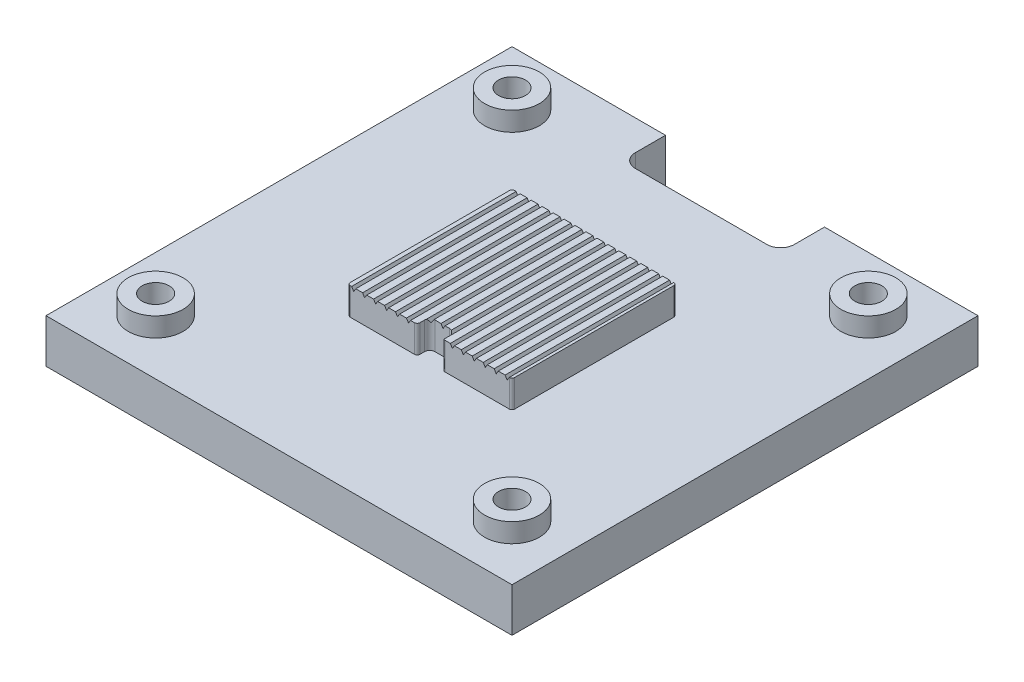
SolidWorks part; units mm, degrees
ref_plane "Front Plane" through (0, 0, 0) normal (0, 0, 1) x (1, 0, 0)
ref_plane "Top Plane" through (0, 0, 0) normal (0, 1, 0) x (1, 0, 0)
ref_plane "Right Plane" through (0, 0, 0) normal (1, 0, 0) x (0, 0, -1)
sketch "Sketch1" plane through (0, 0, 0) normal (0, 1, 0) x (1, 0, 0)
  line L0 (-7.15, 0) -> (7.15, 0) construction
  line L1 (-42.5, 42.5) -> (42.5, 42.5)
  line L2 (-42.5, 42.5) -> (-42.5, -42.5)
  line L3 (-42.5, -42.5) -> (42.5, -42.5)
  line L4 (42.5, 42.5) -> (42.5, -42.5)
  line L5 (-42.5, 42.5) -> (42.5, -42.5) construction
  line L6 (-42.5, -42.5) -> (42.5, 42.5) construction
  line L7 (0, -7.15) -> (0, 7.15) construction
  circle A0 centre (-32.5, 32.5) radius 2.4575
  circle A1 centre (-32.5, -32.5) radius 2.4575
  circle A2 centre (32.5, -32.5) radius 2.4575
  circle A3 centre (32.5, 32.5) radius 2.4575
  point P0 (0, 0)
  dimension "D3" = 4.915
  dimension "D1" = 85
  dimension "D2" = 85
  dimension "D4" = 10
  dimension "D5" = 10
extrude "Boss-Extrude1" add sketch "Sketch1" along normal blind 8
sketch "Sketch2" plane through (0, 0, 0) normal (0, -1, 0) x (1, 0, 0)
  line L0 (0, -7.15) -> (0, 7.15) construction
  line L1 (7.15, 0) -> (-7.15, 0) construction
  circle A0 centre (-32.5, 32.5) radius 3.969
  circle A1 centre (32.5, 32.5) radius 3.969
  circle A2 centre (32.5, -32.5) radius 3.969
  circle A3 centre (-32.5, -32.5) radius 3.969
  dimension "D1" = 7.938
extrude "Cut-Extrude1" cut sketch "Sketch2" against normal blind 4.166
sketch "Sketch3" plane through (0, 8, 0) normal (0, 1, 0) x (1, 0, 0)
  line L0 (0, -7.15) -> (0, 7.15) construction
  line L1 (-7.15, 0) -> (7.15, 0) construction
  circle A0 centre (32.5, -32.5) radius 5
  circle A1 centre (32.5, -32.5) radius 2.4575
  circle A2 centre (32.5, -32.5) radius 2.4575 construction
  circle A3 centre (-32.5, -32.5) radius 2.4575
  circle A4 centre (-32.5, -32.5) radius 5
  circle A5 centre (-32.5, 32.5) radius 5
  circle A6 centre (-32.5, 32.5) radius 2.4575
  circle A7 centre (32.5, 32.5) radius 2.4575
  circle A8 centre (32.5, 32.5) radius 5
  dimension "D1" = 10
extrude "Boss-Extrude2" add sketch "Sketch3" along normal blind 3.5
sketch "Sketch4" plane through (0, 8, 0) normal (0, 1, 0) x (1, 0, 0)
  line L0 (2.2929, -14.5) -> (2.2929, -13.7071)
  line L1 (14.5, -15) -> (2.7929, -15)
  line L2 (15, -14.5) -> (15, 14.5)
  line L3 (14.5, 15) -> (-14.5, 15)
  line L4 (-15, -14.5) -> (-15, 14.5)
  line L5 (15, -15) -> (-15, 15) construction
  line L6 (15, 15) -> (-15, -15) construction
  line L7 (1.2929, -12.7071) -> (-1.2929, -12.7071)
  line L8 (-2.2929, -13.7071) -> (-2.2929, -14.5)
  line L9 (-2.7929, -15) -> (-14.5, -15)
  arc A0 (-14.5, 15) -> (-15, 14.5) centre (-14.5, 14.5) ccw
  arc A1 (15, 14.5) -> (14.5, 15) centre (14.5, 14.5) ccw
  arc A2 (-14.5, -15) -> (-15, -14.5) centre (-14.5, -14.5) cw
  arc A3 (14.5, -15) -> (15, -14.5) centre (14.5, -14.5) ccw
  arc A4 (-2.2929, -14.5) -> (-2.7929, -15) centre (-2.7929, -14.5) cw
  arc A5 (2.2929, -14.5) -> (2.7929, -15) centre (2.7929, -14.5) ccw
  arc A6 (-1.2929, -12.7071) -> (-2.2929, -13.7071) centre (-1.2929, -13.7071) ccw
  arc A7 (2.2929, -13.7071) -> (1.2929, -12.7071) centre (1.2929, -13.7071) ccw
  point P0 (0, 0)
  point P10 (0, -12.7071)
  point P25 (-2.2929, -15)
  point P30 (-2.2929, -12.7071)
  point P33 (2.2929, -12.7071)
  dimension "D4" = 0.5
  dimension "D6" = 0.5
  dimension "D7" = 1
  dimension "D1" = 30
  dimension "D2" = 2.2929
  dimension "D3" = 4.5858
  dimension "D5" = 30
extrude "Boss-Extrude3" add sketch "Sketch4" along normal blind 5
sketch "Sketch5" plane through (0, 8, 0) normal (0, 1, 0) x (1, 0, 0)
  line L0 (42.5, 42.5) -> (-42.5, 42.5) construction
  line L1 (14.5, 42.5) -> (-14.5, 42.5)
  line L2 (14.5, 42.5) -> (14.5, 34.5)
  line L3 (14.5, 34.5) -> (-14.5, 34.5)
  line L4 (-14.5, 42.5) -> (-14.5, 34.5)
  point P6 (0, 34.5)
  dimension "D1" = 29
  dimension "D2" = 8
extrude "Cut-Extrude2" cut sketch "Sketch5" against normal blind 10
fillet "Fillet1" radius 2.5
sketch "Sketch7" plane through (0, 0, -15) normal (0, 0, -1) x (-1, 0, 0)
  line L0 (-14.5, 13) -> (-14.125, 12.38)
  line L1 (-14.125, 12.38) -> (-13.75, 13)
  line L2 (-14.5, 13) -> (14.5, 13) construction
  line L3 (-13.75, 13) -> (-14.5, 13)
  line L4 (-12.5, 13) -> (-12.125, 12.38)
  line L5 (-12.125, 12.38) -> (-11.75, 13)
  line L6 (-11.75, 13) -> (-12.5, 13)
  line L7 (-10.5, 13) -> (-10.125, 12.38)
  line L8 (-10.125, 12.38) -> (-9.75, 13)
  line L9 (-9.75, 13) -> (-10.5, 13)
  line L10 (-8.5, 13) -> (-8.125, 12.38)
  line L11 (-8.125, 12.38) -> (-7.75, 13)
  line L12 (-7.75, 13) -> (-8.5, 13)
  line L13 (-6.5, 13) -> (-6.125, 12.38)
  line L14 (-6.125, 12.38) -> (-5.75, 13)
  line L15 (-5.75, 13) -> (-6.5, 13)
  line L16 (-4.5, 13) -> (-4.125, 12.38)
  line L17 (-4.125, 12.38) -> (-3.75, 13)
  line L18 (-3.75, 13) -> (-4.5, 13)
  line L19 (-2.5, 13) -> (-2.125, 12.38)
  line L20 (-2.125, 12.38) -> (-1.75, 13)
  line L21 (-1.75, 13) -> (-2.5, 13)
  line L22 (-0.5, 13) -> (-0.125, 12.38)
  line L23 (-0.125, 12.38) -> (0.25, 13)
  line L24 (0.25, 13) -> (-0.5, 13)
  line L25 (1.5, 13) -> (1.875, 12.38)
  line L26 (1.875, 12.38) -> (2.25, 13)
  line L27 (2.25, 13) -> (1.5, 13)
  line L28 (3.5, 13) -> (3.875, 12.38)
  line L29 (3.875, 12.38) -> (4.25, 13)
  line L30 (4.25, 13) -> (3.5, 13)
  line L31 (5.5, 13) -> (5.875, 12.38)
  line L32 (5.875, 12.38) -> (6.25, 13)
  line L33 (6.25, 13) -> (5.5, 13)
  line L34 (7.5, 13) -> (7.875, 12.38)
  line L35 (7.875, 12.38) -> (8.25, 13)
  line L36 (8.25, 13) -> (7.5, 13)
  line L37 (9.5, 13) -> (9.875, 12.38)
  line L38 (9.875, 12.38) -> (10.25, 13)
  line L39 (10.25, 13) -> (9.5, 13)
  line L40 (11.5, 13) -> (11.875, 12.38)
  line L41 (11.875, 12.38) -> (12.25, 13)
  line L42 (12.25, 13) -> (11.5, 13)
  line L43 (13.5, 13) -> (13.875, 12.38)
  line L44 (13.875, 12.38) -> (14.25, 13)
  line L45 (14.25, 13) -> (13.5, 13)
  dimension "D1" = 0.375
  dimension "D2" = 0.375
  dimension "D3" = 0.62
  dimension "D4" = 15
extrude "Cut-Extrude3" cut sketch "Sketch7" against normal up to next
